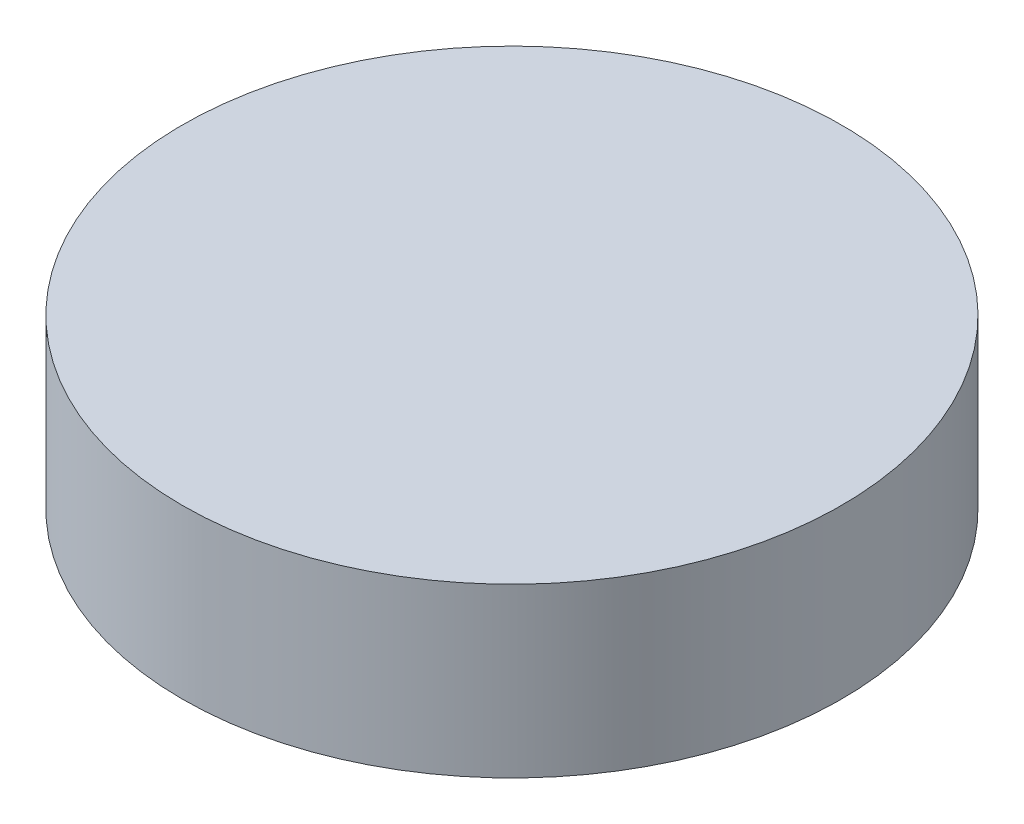
SolidWorks part; units mm, degrees
ref_plane "Front Plane" through (0, 0, 0) normal (0, 0, 1) x (1, 0, 0)
ref_plane "Top Plane" through (0, 0, 0) normal (0, 1, 0) x (1, 0, 0)
ref_plane "Right Plane" through (0, 0, 0) normal (1, 0, 0) x (0, 0, -1)
sketch "Sketch1" plane through (0, 0, 0) normal (0, 1, 0) x (1, 0, 0)
  circle A0 centre (0, 0) radius 69.85
  dimension "D1" = 139.7
extrude "Boss-Extrude1" add sketch "Sketch1" along normal blind 35.56
